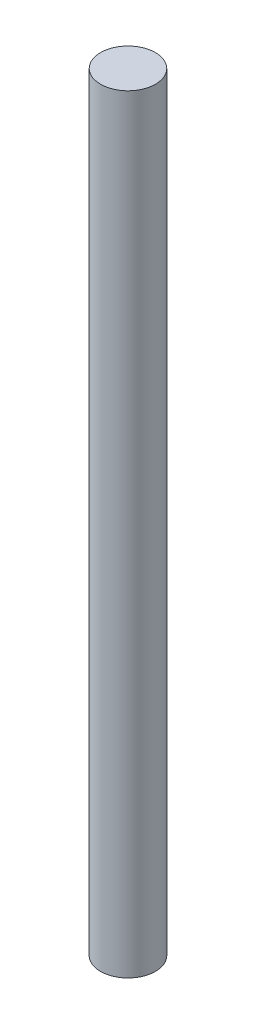
SolidWorks part; units mm, degrees
ref_plane "Front Plane" through (0, 0, 0) normal (0, 0, 1) x (1, 0, 0)
ref_plane "Top Plane" through (0, 0, 0) normal (0, 1, 0) x (1, 0, 0)
ref_plane "Right Plane" through (0, 0, 0) normal (1, 0, 0) x (0, 0, -1)
sketch "Sketch1" plane through (0, 0, 0) normal (0, 1, 0) x (1, 0, 0)
  circle A0 centre (0, 0) radius 2.5
  dimension "D1" = 5
extrude "Boss-Extrude1" add sketch "Sketch1" along normal blind 70
